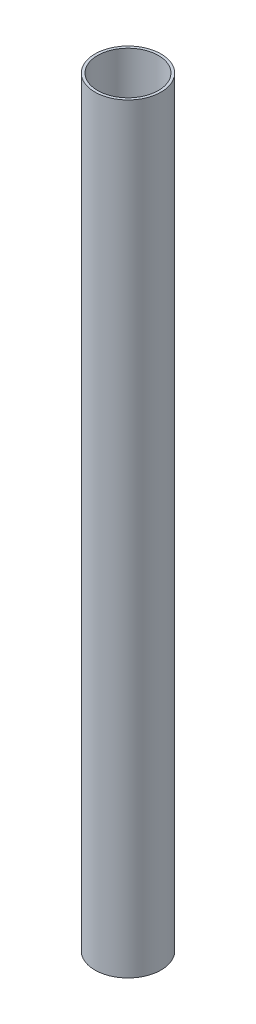
SolidWorks part; units mm, degrees
material "Thornel Mat VMA"
ref_plane "前视基准面" through (0, 0, 0) normal (0, 0, 1) x (1, 0, 0)
ref_plane "上视基准面" through (0, 0, 0) normal (0, 1, 0) x (1, 0, 0)
ref_plane "右视基准面" through (0, 0, 0) normal (1, 0, 0) x (0, 0, -1)
sketch "草图1" plane through (0, 0, 0) normal (0, 1, 0) x (1, 0, 0)
  circle A0 centre (0, 0) radius 12.5
  circle A1 centre (0, 0) radius 11.5
  dimension "D1" = 25
  dimension "D2" = 1
extrude "凸台-拉伸1" add sketch "草图1" along normal blind 287.5
